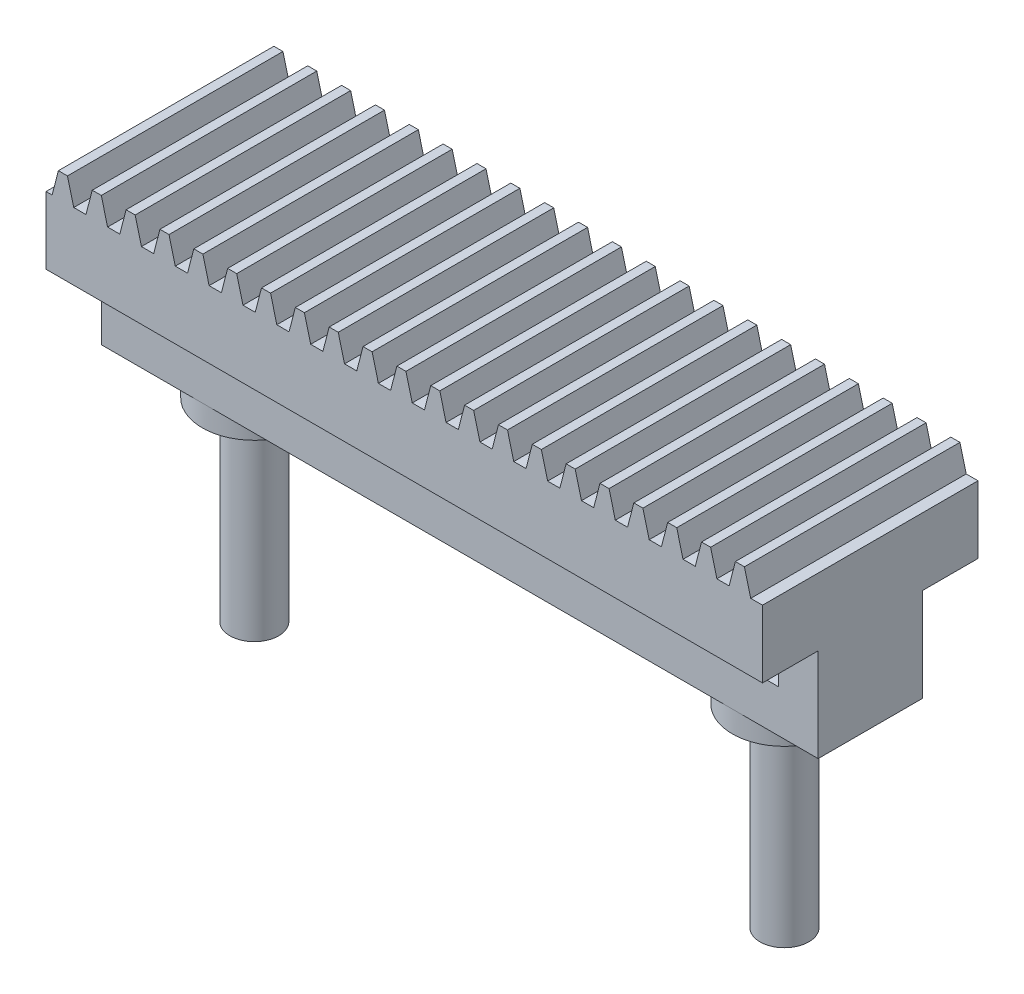
SolidWorks part; units mm, degrees
extrude "Blank" add sketch "BlankSke" against normal blind 20
sketch "BlankSke" plane through (0, 0, 0) normal (0, 0, 1) x (1, 0, 0)
  line L1 (0, 0) -> (100, 0)
  line L2 (0, 0) -> (0, 12.75)
  line L3 (0, 12.75) -> (100, 12.75)
  line L4 (100, 0) -> (100, 12.75)
  dimension "Length" = 100
  dimension "Blank_height" = 12.75
ref_plane "Plane1" through (0, 0, 0) normal (0, 0, 1) x (1, 0, 0)
ref_plane "Plane2" through (0, 0, 0) normal (0, 1, 0) x (1, 0, 0)
ref_plane "Plane3" through (0, 0, 0) normal (1, 0, 0) x (0, 0, -1)
other "Configuration Table"
sketch "HoldingSke" plane through (0, 0, 0) normal (0, 1, 0) x (1, 0, 0)
  line L0 (0, 0) -> (0.0928, 0.6602)
  line L1 (-15, 0) -> (100, 0) construction
  line L2 (0, 0) -> (-2.1039, 2.3779)
  line L3 (0, 0) -> (-11.863, 4.5341)
  line L4 (0, 0) -> (7.9495, 3.3743)
  line L5 (0, 0) -> (-23.7986, -8.8762)
  line L6 (0, 0) -> (-10.5278, -7.1032)
  line L9 (-67.7845, 28.3722) -> (29.0302, 53.4102)
  line L10 (-76.2, 3.8779) -> (-64.95, 3.8779)
  line L11 (0, 0) -> (-20, 0)
  line L12 (-76.2, 101.6) -> (-76.147, 101.6)
  line L13 (24.9733, 27.94) -> (52.9518, 28.4284)
  line L14 (24.9733, 27.94) -> (24.9743, 27.94)
  line L15 (24.9733, 27.94) -> (100.4006, 29.5858)
  circle A0 centre (0, 0) radius 19.05
  circle A1 centre (0, 0) radius 5.625
  circle A2 centre (0, 0) radius 12.7
  dimension "MPH" = 11.25
  dimension "Diameter" = 38.1
  dimension "Num_teeth" = 23
  dimension "Pitch" = 0.6667
  dimension "Show_teeth" = 998
  dimension "Thickness" = 12.7
  dimension "Ap" = 14.5
  dimension "Pitch_height" = 11.25
  dimension "Width" = 20
  dimension "Backlash" = 0.053
  dimension "Addendum_fac" = 1
  dimension "Dedendum_fac" = 1.25
  dimension "Clearance_fac" = 0.25
  dimension "Dedendum_add" = 0.001
  dimension "Length" = 100
  dimension "Module" = 1.5
sketch "TooCutSkeIll" plane through (0, 0, 0) normal (0, 0, 1) x (1, 0, 0)
  line L0 (-1.7134, 12.705) -> (-0.9251, 9.6569)
  line L1 (-0.5611, 9.375) -> (0.5611, 9.375)
  line L2 (0.9251, 9.6569) -> (1.7134, 12.705)
  line L3 (100, 12.75) -> (0, 12.75) construction
  line L4 (0, 0) -> (0, 64.897) construction
  line L5 (-13.208, 11.25) -> (12.954, 11.25) construction
  line L6 (0, 0) -> (100, 0) construction
  line L7 (1.3371, 11.25) -> (1.3371, 48.7463) construction
  line L8 (-1.3371, 11.25) -> (-1.3371, 48.7463) construction
  line L9 (1.7715, 12.75) -> (1.7715, 12.7754)
  line L10 (-1.7715, 12.75) -> (-1.7715, 12.7754)
  line L11 (-1.7715, 12.7754) -> (1.7715, 12.7754)
  arc A0 (0.5611, 9.375) -> (0.9251, 9.6569) centre (0.5611, 9.751) ccw
  arc A1 (-0.9251, 9.6569) -> (-0.5611, 9.375) centre (-0.5611, 9.751) ccw
  arc A2 (1.7715, 12.75) -> (1.7134, 12.705) centre (1.7715, 12.69) ccw
  arc A3 (-1.7134, 12.705) -> (-1.7715, 12.75) centre (-1.7715, 12.69) ccw
  dimension "Pitch_height" = 11.25
  dimension "Addendum_plus" = 1.5254
  dimension "Pressure_angle" = 14.5
  dimension "Gap_width" = 2.6742
  dimension "Dedendum" = 1.875
extrude "ToothCutIll" [suppressed] cut sketch "TooCutSkeIll" against normal through all
sketch "TooCutSkeSim" plane through (0, 0, 0) normal (0, 0, 1) x (1, 0, 0)
  line L0 (0.8522, 9.375) -> (-0.8522, 9.375)
  line L1 (1.7316, 12.7754) -> (0.8522, 9.375)
  line L2 (0, 17.4625) -> (0, 53.467) construction
  line L3 (1.7316, 12.7754) -> (-1.7316, 12.7754)
  line L6 (-1.7316, 12.7754) -> (-0.8522, 9.375)
  line L9 (-1.3371, 11.25) -> (1.3371, 11.25) construction
  line L10 (0, 0) -> (100, 0) construction
  line L11 (1.3371, 11.25) -> (1.3371, 53.467) construction
  line L12 (-1.3371, 11.25) -> (-1.3371, 53.467) construction
  dimension "Pitch_height" = 11.25
  dimension "Addendum_plus" = 1.5254
  dimension "Pressure_angle" = 14.5
  dimension "Gap_width" = 2.6742
  dimension "Dedendum" = 1.875
extrude "ToothCutSim" cut sketch "TooCutSkeSim" against normal through all
pattern_linear "TeethCuts" count 22 spacing 4.7124 along (1, 0, 0) of "ToothCutSim"
sketch "Croquis1" plane through (0, 0, 0) normal (0, 0, 1) x (1, 0, 0)
  line L89 (99.8124, 9.375) -> (98.108, 9.375)
  line L90 (98.108, 9.375) -> (97.2351, 12.75)
  line L91 (97.2351, 12.75) -> (95.9728, 12.75)
  line L92 (95.9728, 12.75) -> (95.1, 9.375)
  line L93 (95.1, 9.375) -> (93.3956, 9.375)
  line L94 (93.3956, 9.375) -> (92.5228, 12.75)
  line L95 (92.5228, 12.75) -> (91.2604, 12.75)
  line L96 (91.2604, 12.75) -> (90.3876, 9.375)
  line L97 (90.3876, 9.375) -> (88.6832, 9.375)
  line L98 (88.6832, 9.375) -> (87.8104, 12.75)
  line L99 (87.8104, 12.75) -> (86.548, 12.75)
  line L100 (86.548, 12.75) -> (85.6752, 9.375)
  line L101 (85.6752, 9.375) -> (83.9708, 9.375)
  line L102 (83.9708, 9.375) -> (83.098, 12.75)
  line L103 (83.098, 12.75) -> (81.8356, 12.75)
  line L104 (81.8356, 12.75) -> (80.9628, 9.375)
  line L105 (80.9628, 9.375) -> (79.2584, 9.375)
  line L106 (79.2584, 9.375) -> (78.3856, 12.75)
  line L107 (78.3856, 12.75) -> (77.1232, 12.75)
  line L108 (77.1232, 12.75) -> (76.2504, 9.375)
  line L109 (76.2504, 9.375) -> (74.546, 9.375)
  line L110 (74.546, 9.375) -> (73.6732, 12.75)
  line L111 (73.6732, 12.75) -> (72.4109, 12.75)
  line L112 (72.4109, 12.75) -> (71.538, 9.375)
  line L113 (71.538, 9.375) -> (69.8336, 9.375)
  line L114 (69.8336, 9.375) -> (68.9608, 12.75)
  line L115 (68.9608, 12.75) -> (67.6985, 12.75)
  line L116 (67.6985, 12.75) -> (66.8256, 9.375)
  line L117 (66.8256, 9.375) -> (65.1213, 9.375)
  line L118 (65.1213, 9.375) -> (64.2484, 12.75)
  line L119 (64.2484, 12.75) -> (62.9861, 12.75)
  line L120 (62.9861, 12.75) -> (62.1132, 9.375)
  line L121 (62.1132, 9.375) -> (60.4089, 9.375)
  line L122 (60.4089, 9.375) -> (59.536, 12.75)
  line L123 (59.536, 12.75) -> (58.2737, 12.75)
  line L124 (58.2737, 12.75) -> (57.4009, 9.375)
  line L125 (57.4009, 9.375) -> (55.6965, 9.375)
  line L126 (55.6965, 9.375) -> (54.8236, 12.75)
  line L127 (54.8236, 12.75) -> (53.5613, 12.75)
  line L128 (53.5613, 12.75) -> (52.6885, 9.375)
  line L129 (52.6885, 9.375) -> (50.9841, 9.375)
  line L130 (50.9841, 9.375) -> (50.1113, 12.75)
  line L131 (50.1113, 12.75) -> (48.8489, 12.75)
  line L132 (48.8489, 12.75) -> (47.9761, 9.375)
  line L133 (47.9761, 9.375) -> (46.2717, 9.375)
  line L134 (46.2717, 9.375) -> (45.3989, 12.75)
  line L135 (45.3989, 12.75) -> (44.1365, 12.75)
  line L136 (44.1365, 12.75) -> (43.2637, 9.375)
  line L137 (43.2637, 9.375) -> (41.5593, 9.375)
  line L138 (41.5593, 9.375) -> (40.6865, 12.75)
  line L139 (40.6865, 12.75) -> (39.4241, 12.75)
  line L140 (39.4241, 12.75) -> (38.5513, 9.375)
  line L141 (38.5513, 9.375) -> (36.8469, 9.375)
  line L142 (36.8469, 9.375) -> (35.9741, 12.75)
  line L143 (35.9741, 12.75) -> (34.7117, 12.75)
  line L144 (34.7117, 12.75) -> (33.8389, 9.375)
  line L145 (33.8389, 9.375) -> (32.1345, 9.375)
  line L146 (32.1345, 9.375) -> (31.2617, 12.75)
  line L147 (31.2617, 12.75) -> (29.9994, 12.75)
  line L148 (29.9994, 12.75) -> (29.1265, 9.375)
  line L149 (29.1265, 9.375) -> (27.4221, 9.375)
  line L150 (27.4221, 9.375) -> (26.5493, 12.75)
  line L151 (26.5493, 12.75) -> (25.287, 12.75)
  line L152 (25.287, 12.75) -> (24.4141, 9.375)
  line L153 (24.4141, 9.375) -> (22.7098, 9.375)
  line L154 (22.7098, 9.375) -> (21.8369, 12.75)
  line L155 (21.8369, 12.75) -> (20.5746, 12.75)
  line L156 (20.5746, 12.75) -> (19.7017, 9.375)
  line L157 (19.7017, 9.375) -> (17.9974, 9.375)
  line L158 (17.9974, 9.375) -> (17.1245, 12.75)
  line L159 (17.1245, 12.75) -> (15.8622, 12.75)
  line L160 (15.8622, 12.75) -> (14.9894, 9.375)
  line L161 (14.9894, 9.375) -> (13.285, 9.375)
  line L162 (13.285, 9.375) -> (12.4121, 12.75)
  line L163 (12.4121, 12.75) -> (11.1498, 12.75)
  line L164 (11.1498, 12.75) -> (10.277, 9.375)
  line L165 (10.277, 9.375) -> (8.5726, 9.375)
  line L166 (8.5726, 9.375) -> (7.6998, 12.75)
  line L167 (7.6998, 12.75) -> (6.4374, 12.75)
  line L168 (6.4374, 12.75) -> (5.5646, 9.375)
  line L169 (5.5646, 9.375) -> (3.8602, 9.375)
  line L170 (3.8602, 9.375) -> (2.9874, 12.75)
  line L171 (2.9874, 12.75) -> (1.725, 12.75)
  line L172 (1.725, 12.75) -> (0.8522, 9.375)
  line L173 (0.8522, 9.375) -> (0, 9.375)
  line L174 (0, 9.375) -> (0, 0)
  line L175 (0, 0) -> (100, 0)
  line L176 (100, 0) -> (100, 10.1006)
  line L177 (100, 10.1006) -> (99.8124, 9.375)
  line L178 (99.8124, 9.375) -> (98.108, 9.375)
  line L179 (98.108, 9.375) -> (97.2351, 12.75)
  line L180 (97.2351, 12.75) -> (95.9728, 12.75)
  line L181 (95.9728, 12.75) -> (95.1, 9.375)
  line L182 (95.1, 9.375) -> (93.3956, 9.375)
  line L183 (93.3956, 9.375) -> (92.5228, 12.75)
  line L184 (92.5228, 12.75) -> (91.2604, 12.75)
  line L185 (91.2604, 12.75) -> (90.3876, 9.375)
  line L186 (90.3876, 9.375) -> (88.6832, 9.375)
  line L187 (88.6832, 9.375) -> (87.8104, 12.75)
  line L188 (87.8104, 12.75) -> (86.548, 12.75)
  line L189 (86.548, 12.75) -> (85.6752, 9.375)
  line L190 (85.6752, 9.375) -> (83.9708, 9.375)
  line L191 (83.9708, 9.375) -> (83.098, 12.75)
  line L192 (83.098, 12.75) -> (81.8356, 12.75)
  line L193 (81.8356, 12.75) -> (80.9628, 9.375)
  line L194 (80.9628, 9.375) -> (79.2584, 9.375)
  line L195 (79.2584, 9.375) -> (78.3856, 12.75)
  line L196 (78.3856, 12.75) -> (77.1232, 12.75)
  line L197 (77.1232, 12.75) -> (76.2504, 9.375)
  line L198 (76.2504, 9.375) -> (74.546, 9.375)
  line L199 (74.546, 9.375) -> (73.6732, 12.75)
  line L200 (73.6732, 12.75) -> (72.4109, 12.75)
  line L201 (72.4109, 12.75) -> (71.538, 9.375)
  line L202 (71.538, 9.375) -> (69.8336, 9.375)
  line L203 (69.8336, 9.375) -> (68.9608, 12.75)
  line L204 (68.9608, 12.75) -> (67.6985, 12.75)
  line L205 (67.6985, 12.75) -> (66.8256, 9.375)
  line L206 (66.8256, 9.375) -> (65.1213, 9.375)
  line L207 (65.1213, 9.375) -> (64.2484, 12.75)
  line L208 (64.2484, 12.75) -> (62.9861, 12.75)
  line L209 (62.9861, 12.75) -> (62.1132, 9.375)
  line L210 (62.1132, 9.375) -> (60.4089, 9.375)
  line L211 (60.4089, 9.375) -> (59.536, 12.75)
  line L212 (59.536, 12.75) -> (58.2737, 12.75)
  line L213 (58.2737, 12.75) -> (57.4009, 9.375)
  line L214 (57.4009, 9.375) -> (55.6965, 9.375)
  line L215 (55.6965, 9.375) -> (54.8236, 12.75)
  line L216 (54.8236, 12.75) -> (53.5613, 12.75)
  line L217 (53.5613, 12.75) -> (52.6885, 9.375)
  line L218 (52.6885, 9.375) -> (50.9841, 9.375)
  line L219 (50.9841, 9.375) -> (50.1113, 12.75)
  line L220 (50.1113, 12.75) -> (48.8489, 12.75)
  line L221 (48.8489, 12.75) -> (47.9761, 9.375)
  line L222 (47.9761, 9.375) -> (46.2717, 9.375)
  line L223 (46.2717, 9.375) -> (45.3989, 12.75)
  line L224 (45.3989, 12.75) -> (44.1365, 12.75)
  line L225 (44.1365, 12.75) -> (43.2637, 9.375)
  line L226 (43.2637, 9.375) -> (41.5593, 9.375)
  line L227 (41.5593, 9.375) -> (40.6865, 12.75)
  line L228 (40.6865, 12.75) -> (39.4241, 12.75)
  line L229 (39.4241, 12.75) -> (38.5513, 9.375)
  line L230 (38.5513, 9.375) -> (36.8469, 9.375)
  line L231 (36.8469, 9.375) -> (35.9741, 12.75)
  line L232 (35.9741, 12.75) -> (34.7117, 12.75)
  line L233 (34.7117, 12.75) -> (33.8389, 9.375)
  line L234 (33.8389, 9.375) -> (32.1345, 9.375)
  line L235 (32.1345, 9.375) -> (31.2617, 12.75)
  line L236 (31.2617, 12.75) -> (29.9994, 12.75)
  line L237 (29.9994, 12.75) -> (29.1265, 9.375)
  line L238 (29.1265, 9.375) -> (27.4221, 9.375)
  line L239 (27.4221, 9.375) -> (26.5493, 12.75)
  line L240 (26.5493, 12.75) -> (25.287, 12.75)
  line L241 (25.287, 12.75) -> (24.4141, 9.375)
  line L242 (24.4141, 9.375) -> (22.7098, 9.375)
  line L243 (22.7098, 9.375) -> (21.8369, 12.75)
  line L244 (21.8369, 12.75) -> (20.5746, 12.75)
  line L245 (20.5746, 12.75) -> (19.7017, 9.375)
  line L246 (19.7017, 9.375) -> (17.9974, 9.375)
  line L247 (17.9974, 9.375) -> (17.1245, 12.75)
  line L248 (17.1245, 12.75) -> (15.8622, 12.75)
  line L249 (15.8622, 12.75) -> (14.9894, 9.375)
  line L250 (14.9894, 9.375) -> (13.285, 9.375)
  line L251 (13.285, 9.375) -> (12.4121, 12.75)
  line L252 (12.4121, 12.75) -> (11.1498, 12.75)
  line L253 (11.1498, 12.75) -> (10.277, 9.375)
  line L254 (10.277, 9.375) -> (8.5726, 9.375)
  line L255 (8.5726, 9.375) -> (7.6998, 12.75)
  line L256 (7.6998, 12.75) -> (6.4374, 12.75)
  line L257 (6.4374, 12.75) -> (5.5646, 9.375)
  line L258 (5.5646, 9.375) -> (3.8602, 9.375)
  line L259 (3.8602, 9.375) -> (2.9874, 12.75)
  line L260 (2.9874, 12.75) -> (1.725, 12.75)
  line L261 (1.725, 12.75) -> (0.8522, 9.375)
  line L262 (0.8522, 9.375) -> (0, 9.375)
  line L263 (0, 9.375) -> (0, 0)
  line L264 (0, 0) -> (100, 0)
  line L265 (100, 0) -> (100, 10.1006)
  line L266 (100, 10.1006) -> (99.8124, 9.375)
  dimension "D1" = 0
extrude "Saliente-Extruir1" add sketch "Croquis1" along normal blind 10
sketch "Croquis12" plane through (100, 0, 0) normal (1, 0, 0) x (0, 0, -1)
  line L4 (20, 10.1006) -> (-10, 10.1006)
  line L5 (-10, 10.1006) -> (-10, 0)
  line L6 (-10, 0) -> (20, 0)
  line L7 (20, 0) -> (20, 10.1006)
  line L8 (20, 10.1006) -> (-10, 10.1006)
  line L9 (-10, 10.1006) -> (-10, 0)
  line L10 (-10, 0) -> (20, 0)
  line L11 (20, 0) -> (20, 10.1006)
  dimension "D1" = 0
extrude "Cortar-Extruir1" cut sketch "Croquis12" against normal blind 0.25 and the other way through all
ref_plane "Plano1" through (0, 0, -5) normal (0, 0, 1) x (1, 0, 0)
sketch "Croquis13" plane through (0, 0, 0) normal (0, -1, 0) x (1, 0, 0)
  line L0 (0, -5) -> (107.4582, -5) construction
  line L1 (0, 2.25) -> (99.75, 2.25)
  line L2 (99.75, 10) -> (99.75, -20) construction
  line L3 (99.75, 2.25) -> (99.75, -12.25)
  line L4 (0, -20) -> (99.75, -20)
  line L5 (99.75, -20) -> (99.75, 10)
  line L6 (99.75, 10) -> (0, 10)
  line L7 (0, 10) -> (0, -20)
  line L11 (0, 10) -> (0, -20) construction
  line L12 (0, 2.25) -> (0, -12.25)
  line L13 (0, -12.25) -> (99.75, -12.25)
  point P11 (99.75, -5)
  dimension "D2" = 7.25
  dimension "D1" = 0
extrude "Saliente-Extruir6" add sketch "Croquis13" along normal blind 13
sketch "Croquis14" plane through (0, -13, 0) normal (0, -1, 0) x (1, 0, 0)
  line L0 (0, -5) -> (108.0787, -5) construction
  line L4 (0, 2.25) -> (0, -12.25)
  line L5 (0, -12.25) -> (99.75, -12.25)
  line L6 (99.75, -12.25) -> (99.75, 2.25)
  line L7 (99.75, 2.25) -> (0, 2.25)
  line L8 (0, 2.25) -> (0, -12.25) construction
  line L9 (0, -12.25) -> (99.75, -12.25) construction
  line L10 (99.75, -12.25) -> (99.75, 2.25) construction
  line L11 (99.75, 2.25) -> (0, 2.25) construction
  circle A0 centre (14, -5) radius 3.4
  circle A1 centre (87.8, -5) radius 3.4
  circle A2 centre (14, -5) radius 7.25
  circle A3 centre (87.8, -5) radius 7.25
  dimension "D2" = 6.8
  dimension "D3" = 73.8
  dimension "D4" = 14
  dimension "D1" = 0
extrude "Saliente-Extruir7" add sketch "Croquis14" along normal blind 3
sketch "Croquis15" plane through (0, -13, 0) normal (0, -1, 0) x (1, 0, 0)
  circle A0 centre (87.8, -5) radius 3.4 construction
  circle A1 centre (14, -5) radius 3.4 construction
  circle A2 centre (87.8, -5) radius 3.4
  circle A3 centre (14, -5) radius 3.4
extrude "Saliente-Extruir8" add sketch "Croquis15" along normal blind 30
sketch "Croquis16" plane through (0, 0, 2.25) normal (0, 0, 1) x (1, 0, 0)
  line L0 (0.926, -5.5) -> (118.1708, -5.5) construction
  line L1 (46.2, -7.1) -> (46.2, -3.9)
  line L2 (34.2, -7.1) -> (28, -7.1)
  line L3 (34.2, -7.1) -> (34.2, -3.9)
  line L4 (34.2, -3.9) -> (28, -3.9)
  line L5 (28, -7.1) -> (28, -3.9)
  line L6 (99.75, 0) -> (0, 0)
  line L7 (0, 0) -> (0, -13)
  line L8 (0, -13) -> (14, -13)
  line L9 (14, -13) -> (87.8, -13)
  line L10 (87.8, -13) -> (99.75, -13)
  line L11 (99.75, -13) -> (99.75, 0)
  line L12 (99.75, 0) -> (0, 0) construction
  line L13 (0, 0) -> (0, -13) construction
  line L14 (0, -13) -> (14, -13) construction
  line L15 (14, -13) -> (87.8, -13) construction
  line L16 (87.8, -13) -> (99.75, -13) construction
  line L17 (99.75, -13) -> (99.75, 0) construction
  line L18 (34.2, -7.1) -> (28, -3.9) construction
  line L19 (34.2, -3.9) -> (28, -7.1) construction
  line L20 (46.2, -3.9) -> (40, -3.9)
  line L21 (40, -7.1) -> (40, -3.9)
  line L22 (46.2, -7.1) -> (40, -7.1)
  line L23 (58.2, -7.1) -> (58.2, -3.9)
  line L24 (58.2, -3.9) -> (52, -3.9)
  line L25 (52, -7.1) -> (52, -3.9)
  line L26 (58.2, -7.1) -> (52, -7.1)
  line L27 (70.2, -7.1) -> (70.2, -3.9)
  line L28 (70.2, -3.9) -> (64, -3.9)
  line L29 (64, -7.1) -> (64, -3.9)
  line L30 (70.2, -7.1) -> (64, -7.1)
  line L31 (82.2, -7.1) -> (82.2, -3.9)
  line L32 (82.2, -3.9) -> (76, -3.9)
  line L33 (76, -7.1) -> (76, -3.9)
  line L34 (82.2, -7.1) -> (76, -7.1)
  line L35 (94.2, -7.1) -> (94.2, -3.9)
  line L36 (94.2, -3.9) -> (88, -3.9)
  line L37 (88, -7.1) -> (88, -3.9)
  line L38 (94.2, -7.1) -> (88, -7.1)
  point P6 (31.1, -5.5)
  dimension "D2" = 7.5
  dimension "D3" = 28
  dimension "D4" = 6.2
  dimension "D5" = 3.2
  dimension "D1" = 0
  dimension "D6" = 6
extrude "Cortar-Extruir2" cut sketch "Croquis16" against normal through all both and the other way through all
equation "' \"Module@HoldingSke\" = 6.35"
equation "' \"Num_teeth@HoldingSke\" = 12"
equation "' \"Ap@HoldingSke\" =  20"
equation "' \"Ap@HoldingSke\" = 20"
equation "' \"Width@HoldingSke\" = 0.25 * 25.4"
equation "' \"Show_teeth@HoldingSke\" = 500"
equation "' \"Backlash@HoldingSke\" = 0.009 * 25.4"
equation "' \"Addendum_fac@HoldingSke\" = 1.0"
equation "' \"Dedendum_fac@HoldingSke\" = 1.25"
equation "' \"Dedendum_add@HoldingSke\" = 0.00005 * 25.4"
equation "' \"Clearance_fac@HoldingSke\" = 0.25"
equation "' \"Pitch_height@HoldingSke\" = 1 * 25.4"
equation "' \"Length@HoldingSke\" = 4.71 * 25.4"
equation "\"Pitch@HoldingSke\" = 1 / \"Module@HoldingSke\""
equation "\"MPH@HoldingSke\" = \"Dedendum_fac@HoldingSke\" / \"Pitch@HoldingSke\" + 2 * \"Dedendum_add@HoldingSke\" + 0.002 * 25.4"
equation "\"MPH@HoldingSke\" = ((sgn( \"MPH@HoldingSke\" - \"Pitch_height@HoldingSke\")+1)*( \"MPH@HoldingSke\" - \"Pitch_height@HoldingSke\"))/2 + \"Pitch_height@HoldingSke\""
equation "\"Blank_height@BlankSke\" = \"Pitch_height@HoldingSke\" + \"Addendum_fac@HoldingSke\"  / \"Pitch@HoldingSke\" "
equation "\"Length@BlankSke\" =  \"Length@HoldingSke\""
equation "\"Face_width@Blank\" = \"Width@HoldingSke\""
equation "\"Pressure_angle@TooCutSkeIll\" = \"Ap@HoldingSke\""
equation "\"Addendum_plus@TooCutSkeIll\" =  \"Addendum_fac@HoldingSke\"  / \"Pitch@HoldingSke\" + 0.001 *25.4"
equation "\"Dedendum@TooCutSkeIll\" = \"Dedendum_fac@HoldingSke\"  / \"Pitch@HoldingSke\""
equation "\"Pitch_height@TooCutSkeIll\" =  \"MPH@HoldingSke\""
equation "\"Gap_width@TooCutSkeIll\" = 3.14159265 / 2 / \"Pitch@HoldingSke\" + 6 * \"Backlash@HoldingSke\""
equation "\"Pressure_angle@TooCutSkeSim\" = \"Ap@HoldingSke\""
equation "\"Addendum_plus@TooCutSkeSim\" =  \"Addendum_fac@HoldingSke\"  / \"Pitch@HoldingSke\" + 0.001 * 25.4"
equation "\"Dedendum@TooCutSkeSim\" = \"Dedendum_fac@HoldingSke\"  / \"Pitch@HoldingSke\""
equation "\"Pitch_height@TooCutSkeSim\" =  \"MPH@HoldingSke\""
equation "\"Gap_width@TooCutSkeSim\" = 3.14159265 / 2 / \"Pitch@HoldingSke\" + 6 * \"Backlash@HoldingSke\""
equation "\"Root_fillet@TooCutSkeIll\" = \"Clearance_fac@HoldingSke\" / \"Pitch@HoldingSke\" + \"Dedendum_add@HoldingSke\""
equation "\"Break_rad@TooCutSkeIll\" = 0.02 / \"Pitch@HoldingSke\" * 2"
equation "\"Linear_pitch@TeethCuts\" = 3.14159265 / \"Pitch@HoldingSke\""
equation "\"Num_teeth@HoldingSke\" = int( ( \"Length@HoldingSke\" + 0 ) / (3.14159265 / \"Pitch@HoldingSke\")) + 0.9999  + 1"
equation " \"Num_teeth@TeethCuts\" = int( \"Show_teeth@HoldingSke\" ) + 1"
equation " \"Num_teeth@TeethCuts\" = ((sgn( \"Num_teeth@TeethCuts\" - \"Num_teeth@HoldingSke\" )-1)*( \"Num_teeth@TeethCuts\" - \"Num_teeth@HoldingSke\" ))/-2+ \"Num_teeth@HoldingSke\""
equation " \"Num_teeth@TeethCuts\" = ((sgn( \"Num_teeth@TeethCuts\" - 2.0)+1)*( \"Num_teeth@TeethCuts\" - 2.0))/2 +2.0"
